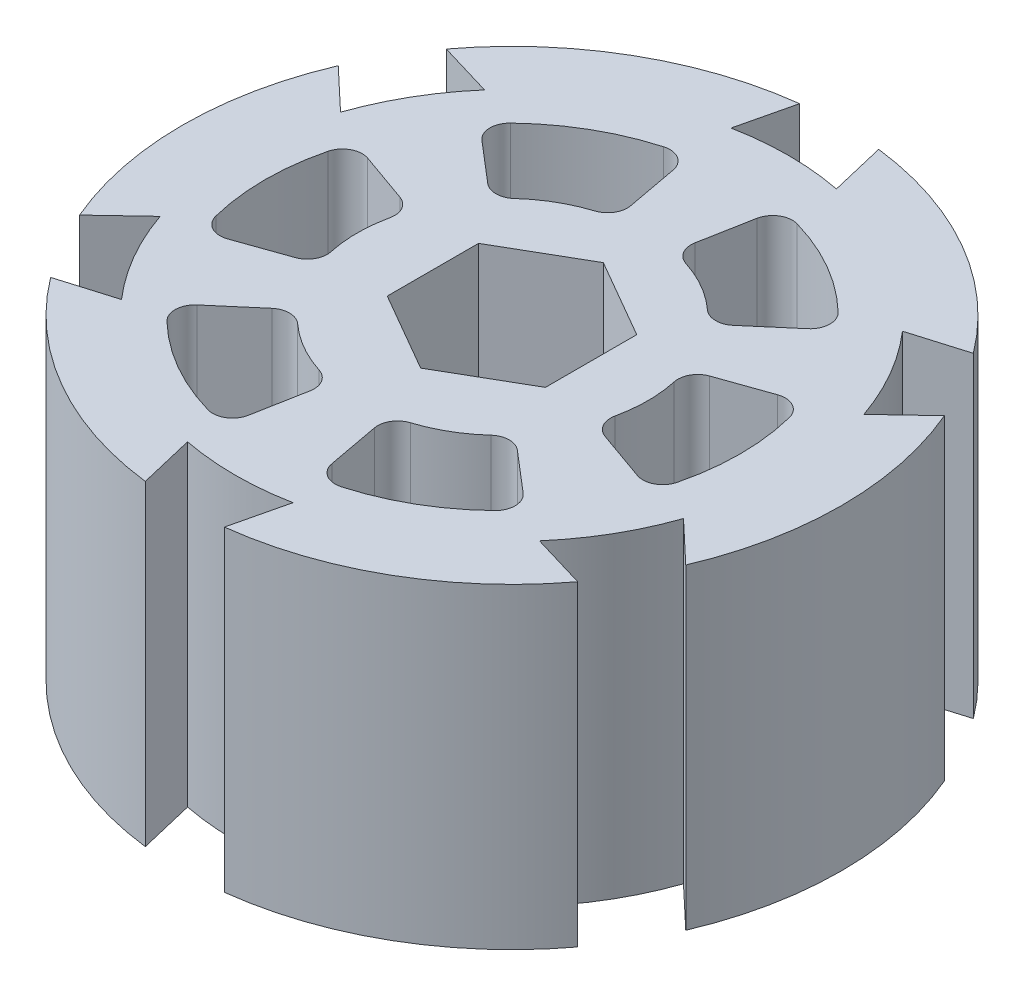
SolidWorks part; units mm, degrees
ref_plane "Front Plane" through (0, 0, 0) normal (0, 0, 1) x (1, 0, 0)
ref_plane "Top Plane" through (0, 0, 0) normal (0, 1, 0) x (1, 0, 0)
ref_plane "Right Plane" through (0, 0, 0) normal (1, 0, 0) x (0, 0, -1)
sketch "Sketch1" plane through (0, 0, 0) normal (0, 1, 0) x (1, 0, 0)
  circle A0 centre (0, 0) radius 25
  dimension "D1" = 50
extrude "Boss-Extrude1" add sketch "Sketch1" along normal blind 24
sketch "Sketch2" plane through (0, 0, 0) normal (0, 1, 0) x (1, 0, 0)
  line L0 (-4, 20.6155) -> (-3, 24.8193)
  line L1 (-3, 24.8193) -> (3, 24.8193) construction
  line L2 (3, 24.8193) -> (4, 20.6155)
  line L3 (0, 0) -> (0, 27.2938) construction
  line L4 (-4, 20.6155) -> (4, 20.6155) construction
  circle A0 centre (0, 0) radius 21
  circle A1 centre (0, 0) radius 25 construction
  circle A2 centre (0, 0) radius 25
  point P10 (0, 20.6155)
  point P12 (0, 24.8193)
  dimension "D3" = 4
  dimension "D1" = 6
  dimension "D2" = 8
extrude "Cut-Extrude3" cut sketch "Sketch2" against normal blind 2 and the other way through all contours L2 A2 L0 A0
pattern_circular "CirPattern1" count 6 over 360 about axis through (0, 0, 0) along (0, 1, 0) of "Cut-Extrude3"
sketch "Sketch3" plane through (0, 0, 0) normal (0, 1, 0) x (1, 0, 0)
  line L1 (9.0496, 7.7366) -> (12.1079, 10.3513)
  line L2 (2.1753, 11.7055) -> (2.9105, 15.6614)
  line L3 (0, 0) -> (12.167, 21.0739) construction
  circle A0 centre (0, 0) radius 17.5
  circle A1 centre (0, 0) radius 10.5
  arc A2 (19.9942, 15.0077) -> (3, 24.8193) centre (0, 0) ccw construction
  arc A3 (7.0655, 7.7672) -> (9.0496, 7.7366) centre (8.0748, 8.8768) ccw
  arc A5 (3.1938, 10.0025) -> (2.1753, 11.7055) centre (3.6501, 11.4314) cw
  arc A6 (4.7964, 16.8299) -> (2.9105, 15.6614) centre (4.3853, 15.3873) ccw
  arc A7 (12.1769, 12.5687) -> (12.1079, 10.3513) centre (11.1332, 11.4914) cw
  point P16 (12.5, 21.6506)
  dimension "D1" = 35
  dimension "D2" = 7
  dimension "D3" = 3
  dimension "D4" = 3
extrude "Cut-Extrude4" cut sketch "Sketch3" along normal up to surface (24 mm away) contours A1 L3 A0 L2 A5 | L3 A1 A3 L1 A0
pattern_circular "CirPattern5" count 6 over 360 about axis through (-0.2623, 0, 0.4542) along (0, 1, 0) of "Cut-Extrude4"
sketch "Sketch5" plane through (0, 24, 0) normal (0, 1, 0) x (1, 0, 0)
  line L1 (0, 6.9282) -> (-6, 3.4641)
  line L2 (-6, 3.4641) -> (-6, -3.4641)
  line L3 (-6, -3.4641) -> (0, -6.9282)
  line L4 (0, -6.9282) -> (6, -3.4641)
  line L5 (6, -3.4641) -> (6, 3.4641)
  line L6 (6, 3.4641) -> (0, 6.9282)
  circle A0 centre (0, 0) radius 6 construction
  dimension "D1" = 12
extrude "Cut-Extrude5" cut sketch "Sketch5" against normal blind 18
sketch "Sketch6" plane through (0, 6, 0) normal (0, 1, 0) x (1, 0, 0)
  circle A0 centre (0, 0) radius 1.9
  dimension "D1" = 3.8
extrude "Cut-Extrude6" cut sketch "Sketch6" against normal blind 18
